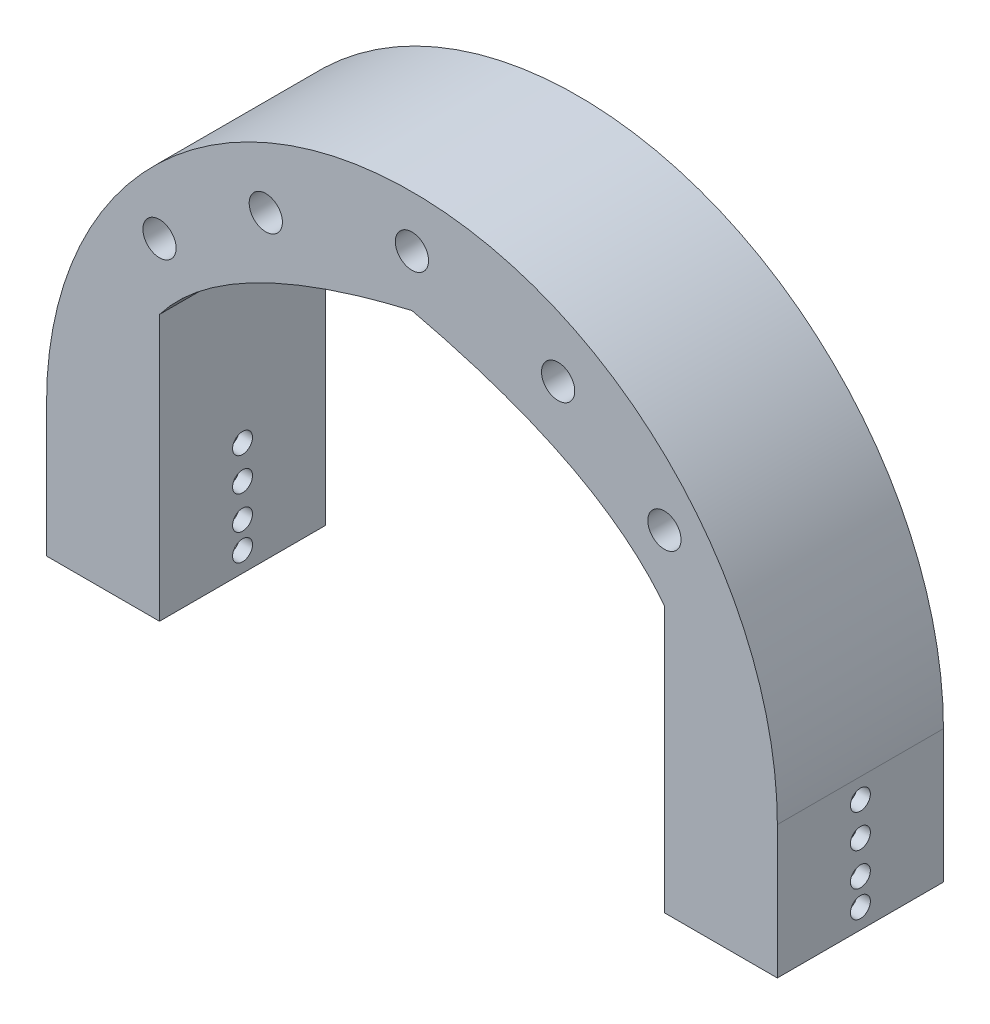
SolidWorks part; units mm, degrees
ref_plane "Front Plane" through (0, 0, 0) normal (0, 0, 1) x (1, 0, 0)
ref_plane "Top Plane" through (0, 0, 0) normal (0, 1, 0) x (1, 0, 0)
ref_plane "Right Plane" through (0, 0, 0) normal (1, 0, 0) x (0, 0, -1)
sketch "Sketch1" plane through (0, 0, 0) normal (0, 0, 1) x (1, 0, 0)
  line L0 (0, 0) -> (-55, 0) construction
  line L1 (0, 50) -> (0, -50) construction
  line L2 (-55, 0) -> (-38, 0)
  line L3 (-38, 20) -> (-38, 0)
  line L4 (38, 20) -> (38, 0)
  line L5 (38, 0) -> (55, 0)
  arc A0 (55, 0) -> (-55, 0) centre (0, 0) ccw
  spline S0 degree 2 poles (0, 39.5) (-28.1676, 32.9266) (-38, 20) knots 0 0 0 0.33145 0.33145 0.33145
  spline S1 degree 2 poles (0, 39.5) (28.1676, 32.9266) (38, 20) knots 0 0 0 0.33145 0.33145 0.33145
  dimension "D1" = 39.5
  dimension "D2" = 110
  dimension "D5" = 38
  dimension "D3" = 20
extrude "Boss-Extrude2" add sketch "Sketch1" along normal mid plane 25
sketch "Sketch2" plane through (0, 0, 0) normal (0, -1, 0) x (1, 0, 0)
  line L1 (38, 12.5) -> (55, 12.5)
  line L2 (38, 12.5) -> (38, -12.5)
  line L3 (38, -12.5) -> (55, -12.5)
  line L4 (55, 12.5) -> (55, -12.5)
  line L5 (-38, -12.5) -> (-55, -12.5)
  line L6 (-38, -12.5) -> (-38, 12.5)
  line L7 (-38, 12.5) -> (-55, 12.5)
  line L8 (-55, -12.5) -> (-55, 12.5)
extrude "Boss-Extrude3" add sketch "Sketch2" along normal blind 20
sketch "Sketch3" plane through (0, -20, 0) normal (0, -1, 0) x (1, 0, 0)
  line L0 (-38, 12.5) -> (-55, 12.5) construction
  line L1 (-53, 9.5) -> (-40, 9.5)
  line L2 (-53, 9.5) -> (-53, -9.5)
  line L3 (-53, -9.5) -> (-40, -9.5)
  line L4 (-40, 9.5) -> (-40, -9.5)
  line L5 (-55, 12.5) -> (-55, -12.5) construction
  line L6 (-38, -12.5) -> (-38, 12.5) construction
  line L7 (-55, -12.5) -> (-38, -12.5) construction
  line L8 (0, 27.0941) -> (0, -40.6607) construction
  line L9 (53, -9.5) -> (40, -9.5)
  line L10 (53, 9.5) -> (53, -9.5)
  line L11 (53, 9.5) -> (40, 9.5)
  line L12 (40, 9.5) -> (40, -9.5)
  dimension "D1" = 3
  dimension "D2" = 2
  dimension "D3" = 2
  dimension "D4" = 3
extrude "Cut-Extrude1" cut sketch "Sketch3" against normal blind 30
sketch "Sketch4" plane through (-55, 0, 0) normal (-1, 0, 0) x (0, 0, 1)
  line L0 (0, 0) -> (0, -1.2343) construction
  line L1 (0, -20) -> (0, 0) construction
  line L2 (12.5, -20) -> (-12.5, -20) construction
  line L3 (12.5, 0) -> (-12.5, 0) construction
  circle A0 centre (0, -3) radius 1.5
  circle A1 centre (0, -17) radius 1.5
  circle A2 centre (0, -8) radius 1.5
  circle A3 centre (0, -13) radius 1.5
  dimension "D1" = 3
  dimension "D2" = 3
  dimension "D4" = 3
  dimension "D3" = 3
  dimension "D5" = 3
extrude "Cut-Extrude2" cut sketch "Sketch4" against normal through all
sketch "Sketch5" plane through (0, 0, 12.5) normal (0, 0, 1) x (1, 0, 0)
  line L0 (0, 55) -> (0, 39.5) construction
  line L1 (-38, 20) -> (-38, 39.7618) construction
  line L2 (38, 20) -> (38, 39.7618) construction
  line L3 (-22, 32.1247) -> (-22, 50.4083) construction
  line L4 (22, 32.1247) -> (22, 50.4083) construction
  arc A0 (55, 0) -> (-55, 0) centre (0, 0) ccw construction
  circle A1 centre (0, 47.25) radius 2.5
  circle A2 centre (-38, 29.8809) radius 2.5
  circle A3 centre (38, 29.8809) radius 2.5
  circle A4 centre (-22, 41.2665) radius 2.5
  circle A5 centre (22, 41.2665) radius 2.5
  parabola Q0 (-38, 20) -> (0, 39.5) focus (-30.2821, 8.8103) apex (-41.8802, 12.829) construction
  dimension "D1" = 5
  dimension "D2" = 5
  dimension "D4" = 5
  dimension "D3" = 22
extrude "Cut-Extrude3" cut sketch "Sketch5" against normal blind 30
